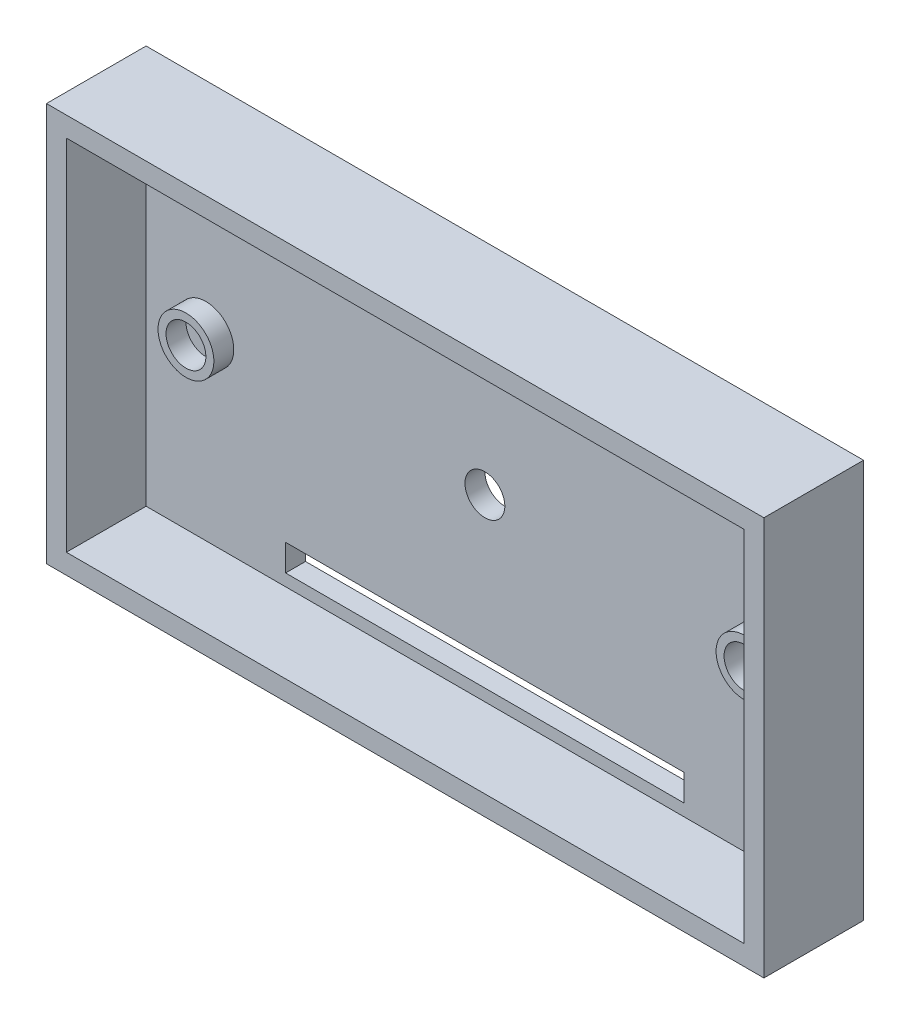
SolidWorks part; units mm, degrees
material "ABS"
ref_plane "Front Plane" through (0, 0, 0) normal (0, 0, 1) x (1, 0, 0)
ref_plane "Top Plane" through (0, 0, 0) normal (0, 1, 0) x (1, 0, 0)
ref_plane "Right Plane" through (0, 0, 0) normal (1, 0, 0) x (0, 0, -1)
sketch "Sketch1" plane through (0, 0, 0) normal (0, 0, 1) x (1, 0, 0)
  line L1 (-57.15, -31.75) -> (57.15, -31.75)
  line L2 (-57.15, -31.75) -> (-57.15, 31.75)
  line L3 (-57.15, 31.75) -> (57.15, 31.75)
  line L4 (57.15, -31.75) -> (57.15, 31.75)
  line L5 (0, 31.75) -> (0, -31.75) construction
  line L6 (-57.15, 0) -> (57.15, 0) construction
  point P0 (0, 0)
  dimension "D1" = 63.5
  dimension "D2" = 114.3
extrude "Boss-Extrude1" add sketch "Sketch1" along normal blind 3.175
sketch "Sketch2" plane through (0, 0, 3.175) normal (0, 0, 1) x (1, 0, 0)
  line L4 (-57.15, -31.75) -> (57.15, -31.75) construction
  line L5 (57.15, -31.75) -> (57.15, 31.75) construction
  line L6 (-57.15, 31.75) -> (-57.15, -31.75) construction
  line L7 (57.15, 31.75) -> (-57.15, 31.75) construction
  line L8 (53.975, -28.575) -> (53.975, 28.575)
  line L9 (53.975, 28.575) -> (-53.975, 28.575)
  line L10 (-53.975, 28.575) -> (-53.975, -28.575)
  line L11 (-53.975, -28.575) -> (53.975, -28.575)
  line L12 (53.975, -28.575) -> (53.975, 28.575)
  line L13 (53.975, 28.575) -> (-53.975, 28.575)
  line L14 (-53.975, 28.575) -> (-53.975, -28.575)
  line L15 (-53.975, -28.575) -> (53.975, -28.575)
  line L16 (-57.15, -31.75) -> (57.15, -31.75)
  line L17 (57.15, -31.75) -> (57.15, 31.75)
  line L18 (-57.15, 31.75) -> (-57.15, -31.75)
  line L19 (57.15, 31.75) -> (-57.15, 31.75)
  dimension "D1" = 3.175
extrude "Boss-Extrude2" add sketch "Sketch2" along normal blind 12.7
sketch "Sketch3" plane through (0, 0, 0) normal (0, 0, -1) x (-1, 0, 0)
  line L0 (-57.15, -31.75) -> (-57.15, 31.75) construction
  line L1 (-31.75, 26.67) -> (31.75, 26.67)
  line L2 (-31.75, 26.67) -> (-31.75, 22.4367)
  line L3 (-31.75, 22.4367) -> (31.75, 22.4367)
  line L4 (31.75, 26.67) -> (31.75, 22.4367)
  line L6 (57.15, 31.75) -> (57.15, -31.75) construction
  line L7 (-57.15, 31.75) -> (57.15, 31.75) construction
  line L8 (8.7312, 0) -> (-8.7312, 0) construction
  line L9 (-31.75, -22.4367) -> (31.75, -22.4367)
  line L10 (31.75, -26.67) -> (31.75, -22.4367)
  line L11 (-31.75, -26.67) -> (31.75, -26.67)
  line L12 (-31.75, -26.67) -> (-31.75, -22.4367)
  circle A0 centre (0, 0) radius 3.175
  dimension "D1" = 6.35
  dimension "D2" = 25.4
  dimension "D3" = 25.4
  dimension "D4" = 5.08
  dimension "D5" = 4.2333
extrude "Cut-Extrude1" cut sketch "Sketch3" against normal up to next
sketch "Sketch4" plane through (0, 0, 3.175) normal (0, 0, 1) x (1, 0, 0)
  line L0 (0, -8.7312) -> (0, 8.7312) construction
  circle A0 centre (44.45, 0) radius 3.175
  circle A1 centre (44.45, 0) radius 4.445
  circle A2 centre (-44.45, 0) radius 4.445
  circle A3 centre (-44.45, 0) radius 3.175
  dimension "D1" = 6.35
  dimension "D2" = 1.27
  dimension "D3" = 44.45
extrude "Boss-Extrude3" add sketch "Sketch4" along normal blind 3.175
